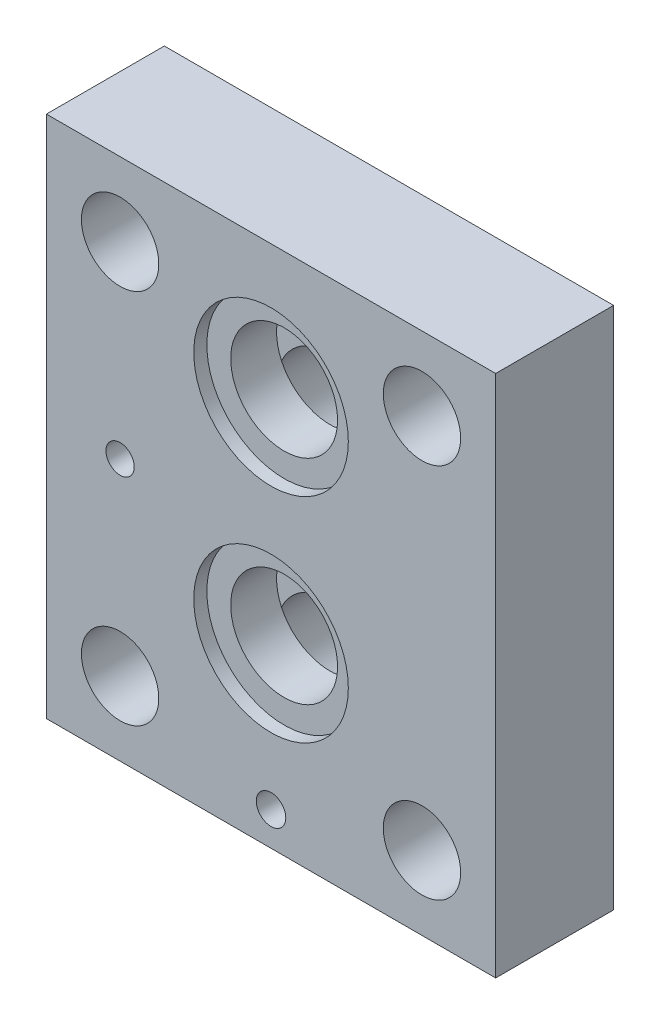
SolidWorks part; units mm, degrees
ref_plane "Front Plane" through (0, 0, 0) normal (1, 0, 0) x (0, 1, 0)
ref_plane "Top Plane" through (0, 0, 0) normal (0, 0, 1) x (0, 1, 0)
ref_plane "Right Plane" through (0, 0, 0) normal (0, 1, 0) x (-1, 0, 0)
sketch "Sketch1" plane through (0, 0, 0) normal (0, 0, 1) x (0, 1, 0)
  line L1 (-56.388, -48.387) -> (56.388, -48.387)
  line L2 (-56.388, -48.387) -> (-56.388, 48.387)
  line L3 (-56.388, 48.387) -> (56.388, 48.387)
  line L4 (56.388, -48.387) -> (56.388, 48.387)
  line L5 (-56.388, -48.387) -> (56.388, 48.387) construction
  line L6 (-56.388, 48.387) -> (56.388, -48.387) construction
  point P0 (0, 0)
extrude "Boss-Extrude1" add sketch "Sketch1" along normal mid plane 25.4
sketch "Sketch2" plane through (0, 0, 0) normal (0, 0, 1) x (0, 1, 0)
  circle A0 centre (-40.513, -32.512) radius 8.3344
extrude "Cut-Extrude2" cut sketch "Sketch2" along normal up to next from offset 12.7
sketch "Sketch3" plane through (0, 0, 0) normal (0, 0, 1) x (0, 1, 0)
  circle A0 centre (40.513, -32.512) radius 8.3344
  circle A1 centre (-40.513, 32.512) radius 8.3344
  circle A2 centre (40.513, 32.512) radius 8.3344
extrude "Cut-Extrude4" cut sketch "Sketch3" along normal up to next from offset 12.7
sketch "Sketch4" plane through (0, 0, 0) normal (0, 0, 1) x (0, 1, 0)
  circle A0 centre (-27.813, 0) radius 11.5094
extrude "Cut-Extrude6" cut sketch "Sketch4" along normal blind 12.7 from offset 12.7
sketch "Sketch5" plane through (0, 0, 0) normal (0, 0, 1) x (0, 1, 0)
  circle A0 centre (18.161, 0) radius 11.5094
extrude "Cut-Extrude8" cut sketch "Sketch5" along normal blind 12.7 from offset 12.7
sketch "Sketch6" plane through (0, 0, 0) normal (0, 0, 1) x (0, 1, 0)
  circle A0 centre (-18.161, 0) radius 11.5094
extrude "Cut-Extrude10" cut sketch "Sketch6" against normal blind 12.7 from offset 12.7
sketch "Sketch7" plane through (0, 0, 0) normal (0, 0, 1) x (0, 1, 0)
  circle A0 centre (27.813, 0) radius 11.5094
extrude "Cut-Extrude12" cut sketch "Sketch7" against normal blind 12.7 from offset 12.7
sketch "Sketch8" plane through (0, 0, 0) normal (0, 0, 1) x (0, 1, 0)
  circle A0 centre (-18.161, 0) radius 16.6497
extrude "Cut-Extrude14" cut sketch "Sketch8" against normal blind 2.8194 from offset 12.7
sketch "Sketch9" plane through (0, 0, 0) normal (0, 0, 1) x (0, 1, 0)
  circle A0 centre (27.813, 0) radius 16.6497
extrude "Cut-Extrude16" cut sketch "Sketch9" against normal blind 2.8194 from offset 12.7
sketch "Sketch10" plane through (0, 0, 0) normal (0, 0, 1) x (0, 1, 0)
  circle A0 centre (49.149, 0) radius 3.5719
extrude "Cut-Extrude18" cut sketch "Sketch10" along normal blind 7.874 from offset 12.7
sketch "Sketch11" plane through (0, 0, 0) normal (0, 0, 1) x (0, 1, 0)
  circle A0 centre (0, -32.512) radius 3.6989
extrude "Cut-Extrude20" cut sketch "Sketch11" along normal blind 7.874 from offset 12.7
sketch "Sketch12" plane through (0, 0, 0) normal (0, 0, 1) x (0, 1, 0)
  circle A0 centre (-49.149, 0) radius 3.175
extrude "Cut-Extrude22" cut sketch "Sketch12" against normal blind 7.874 from offset 12.7
sketch "Sketch13" plane through (0, 0, 0) normal (0, 0, 1) x (0, 1, 0)
  circle A0 centre (0, 32.512) radius 3.048
extrude "Cut-Extrude24" cut sketch "Sketch13" against normal blind 7.874 from offset 12.7
